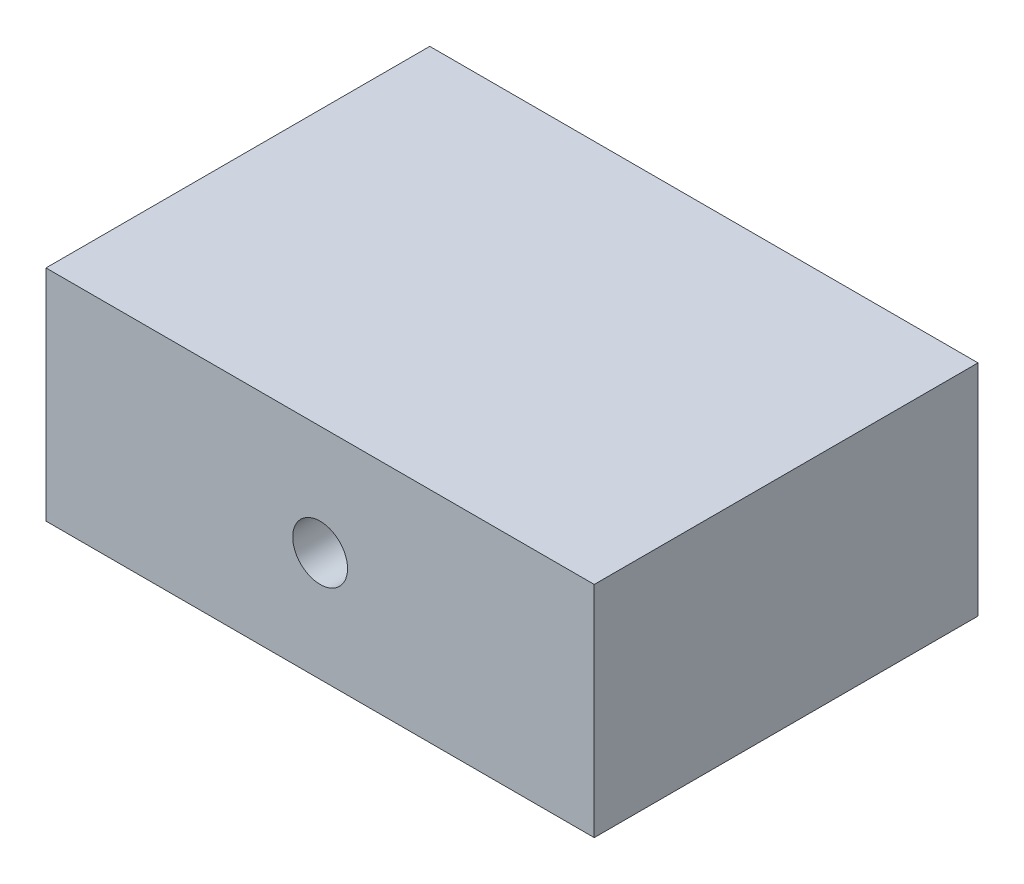
SolidWorks part; units mm, degrees
ref_plane "Front Plane" through (0, 0, 0) normal (0, 0, 1) x (1, 0, 0)
ref_plane "Top Plane" through (0, 0, 0) normal (0, 1, 0) x (1, 0, 0)
ref_plane "Right Plane" through (0, 0, 0) normal (1, 0, 0) x (0, 0, -1)
sketch "Sketch1" plane through (0, 0, 0) normal (0, 0, 1) x (1, 0, 0)
  line L1 (250, -100) -> (-250, -100)
  line L2 (250, -100) -> (250, 100)
  line L3 (250, 100) -> (-250, 100)
  line L4 (-250, -100) -> (-250, 100)
  line L5 (250, -100) -> (-250, 100) construction
  line L6 (250, 100) -> (-250, -100) construction
  circle A0 centre (0, 0) radius 25
  point P0 (0, 0)
  dimension "D3" = 50
  dimension "D1" = 200
  dimension "D2" = 500
extrude "Boss-Extrude1" add sketch "Sketch1" along normal blind 350
equation "\"rover_width\"= 800.0mm"
equation "\"rover_length\"= 1000.0mm"
equation "\"frame_width\"= 350.0mm"
equation "\"frame_height\"= 200.0mm"
equation "\"ground_clearance\"= 400.0mm"
equation "\"swingarm_thickness\"= 5.0mm"
equation "\"steering_asm_height\"= 90.92mm"
equation "\"rear_steering_mount_neck_height\"= 10.0mm"
equation "\"front_steering_mount_base_length\"= 81.18035315337238mm"
equation "\"corner_wheel_asm_height\"= 250.0mm"
equation "\"middle_wheel_shaft_diameter\"= 41.97mm"
equation "\"middle_wheel_shaft_length\"= 80.18mm"
equation "\"middle_wheel_shaft_overhang\"= 10.0mm"
equation "\"middle_wheel_clearance\"= 4.0mm"
equation "\"wheel_diameter\"= 200.0mm"
equation "\"wheel_thickness\"= 83.89mm"
equation "\"linkage_thickness\"= 20.0mm"
equation "\"linkage_width\"= 30.0mm"
equation "\"linkage_wall_thickness\"= 3.0mm"
equation "\"linkage_mount_base_length\"= 10.0mm"
equation "\"linkage_mount_bolt_diameter\"= 10.0mm"
equation "\"upper_shaft_diameter\"= 50.0mm"
equation "\"upper_shaft_frame_clearance\"= 3.0mm"
equation "\"upper_shaft_overhang\"= 3.0mm"
equation "\"lower_shaft_diameter\"= 35.0mm"
equation "\"lower_shaft_overhang\"= 4.5mm"
equation "\"pivot_housing_min_wall_thickness\"= 3.0mm"
equation "\"pivot_housing_bolt_diameter\"= 10.0mm"
equation "\"upper_pivot_housing_num_bolts\"= 12.0"
equation "\"lower_pivot_housing_num_bolts\"= 8.0"
equation "\"upper_bearing_diameter\"= 65.0mm"
equation "\"upper_bearing_outer_race_inner_diameter\"= 61.0mm"
equation "\"upper_bearing_thickness\"= 7.0mm"
equation "\"lower_bearing_diameter\"= 47.0mm"
equation "\"lower_bearing_outer_race_inner_diameter\"= 44.0mm"
equation "\"lower_bearing_thickness\"= 7.0mm"
equation "\"upper_ret_ring_inner_diameter\"= 22.9mm"
equation "\"upper_ret_ring_thickness\"= 2.0mm"
equation "\"lower_ret_ring_inner_diameter\"= 16.1mm"
equation "\"lower_ret_ring_thickness\"= 1.5mm"
equation "\"D1@Sketch1\"=\"frame_height\""
equation "\"D2@Sketch1\"=\"frame_height\"*2.5"
equation "\"D3@Sketch1\"=\"upper_shaft_diameter\""
equation "\"D1@Boss-Extrude1\"=\"frame_width\""
